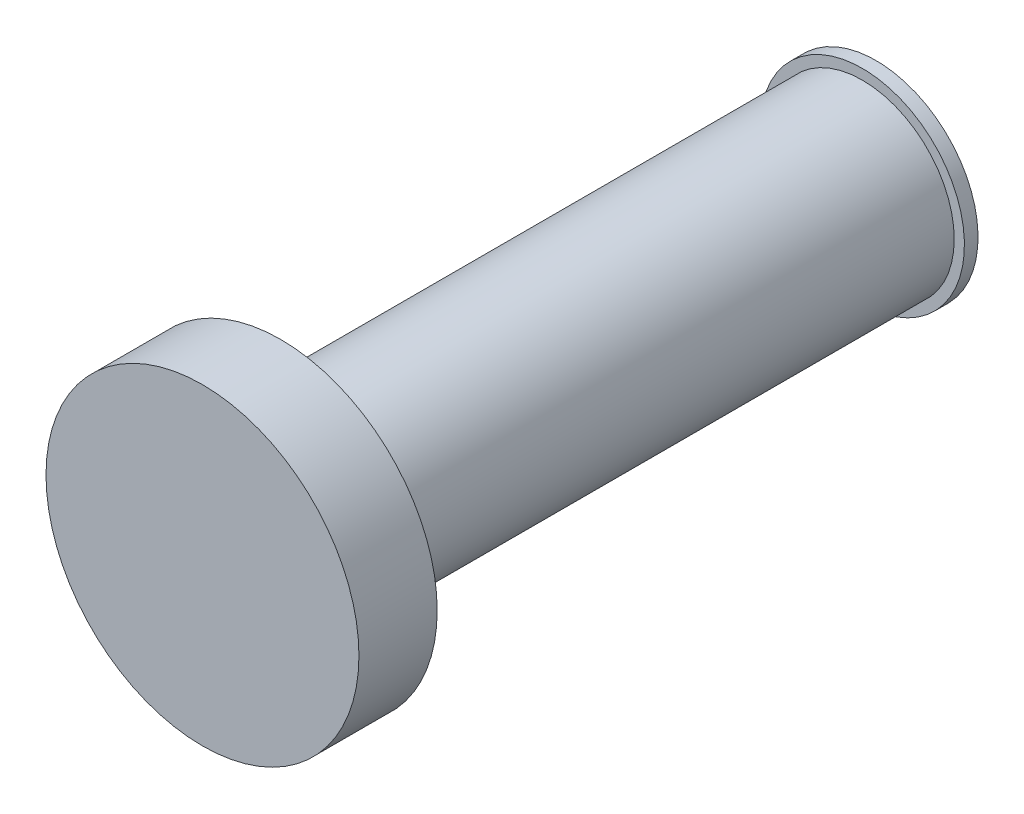
SolidWorks part; units mm, degrees
ref_plane "Front Plane" through (0, 0, 0) normal (0, 0, 1) x (1, 0, 0)
ref_plane "Top Plane" through (0, 0, 0) normal (0, 1, 0) x (1, 0, 0)
ref_plane "Right Plane" through (0, 0, 0) normal (1, 0, 0) x (0, 0, -1)
sketch "Sketch1" plane through (0, 0, 0) normal (0, 0, 1) x (1, 0, 0)
  circle A0 centre (0, 0) radius 1.35
  dimension "D1" = 2.7
extrude "Boss-Extrude1" add sketch "Sketch1" along normal mid plane 8.55
sketch "Sketch2" plane through (0, 0, 4.275) normal (0, 0, 1) x (1, 0, 0)
  circle A0 centre (0, 0.024) radius 2.3
  dimension "D1" = 4.6
extrude "Boss-Extrude2" add sketch "Sketch2" along normal blind 1.15
sketch "Sketch3" plane through (0, 0, -4.275) normal (0, 0, -1) x (-1, 0, 0)
  circle A0 centre (0, 0) radius 1.5
  dimension "D1" = 3
extrude "Boss-Extrude3" add sketch "Sketch3" along normal blind 1.15
sketch "Sketch4" plane through (0, 0, 0) normal (1, 0, 0) x (0, 0, -1)
  line L0 (4.275, 0) -> (5.425, 0) construction
  line L1 (4.275, 1.5) -> (4.275, -1.5) construction
  line L2 (5.425, -1.5) -> (5.425, 1.5) construction
  line L3 (5.225, 0) -> (5.225, 0.2)
  line L4 (4.475, 1.5) -> (4.475, -1.5)
  line L5 (5.425, 1.5) -> (4.275, 1.5) construction
  line L6 (4.275, -1.5) -> (5.425, -1.5) construction
  line L7 (4.475, 1.5) -> (5.225, 0.2)
  line L8 (4.475, 1.5) -> (5.425, 1.5)
  line L9 (5.425, 1.5) -> (5.425, 0)
  dimension "D1" = 0.2
  dimension "D2" = 0.2
  dimension "D3" = 0.2
revolve "Cut-Revolve1" cut sketch "Sketch4" angle 360 about L0
